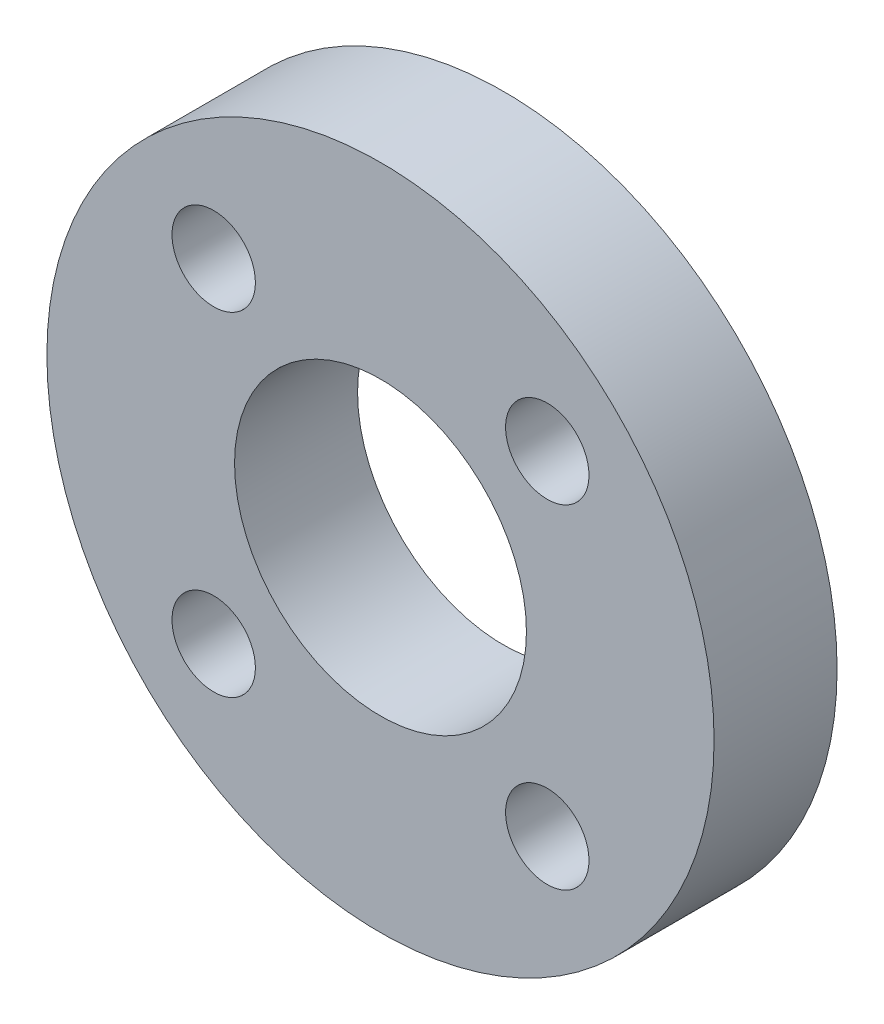
SolidWorks part; units mm, degrees
ref_plane "Front Plane" through (0, 0, 0) normal (0, 0, 1) x (1, 0, 0)
ref_plane "Top Plane" through (0, 0, 0) normal (0, 1, 0) x (1, 0, 0)
ref_plane "Right Plane" through (0, 0, 0) normal (1, 0, 0) x (0, 0, -1)
sketch "Sketch1" plane through (0, 0, 0) normal (0, 0, 1) x (1, 0, 0)
  line L1 (-8, -8) -> (8, -8) construction
  line L2 (-8, -8) -> (-8, 8) construction
  line L3 (-8, 8) -> (8, 8) construction
  line L4 (8, -8) -> (8, 8) construction
  line L5 (0, 8) -> (0, -8) construction
  line L6 (-8, 0) -> (8, 0) construction
  circle A0 centre (0, 0) radius 7
  circle A1 centre (0, 0) radius 16
  circle A2 centre (-8, 8) radius 2
  circle A3 centre (8, 8) radius 2
  circle A4 centre (8, -8) radius 2
  circle A5 centre (-8, -8) radius 2
  dimension "D1" = 32
  dimension "D2" = 14
  dimension "D4" = 4
  dimension "D3" = 16
extrude "Boss-Extrude1" add sketch "Sketch1" along normal blind 5.9
